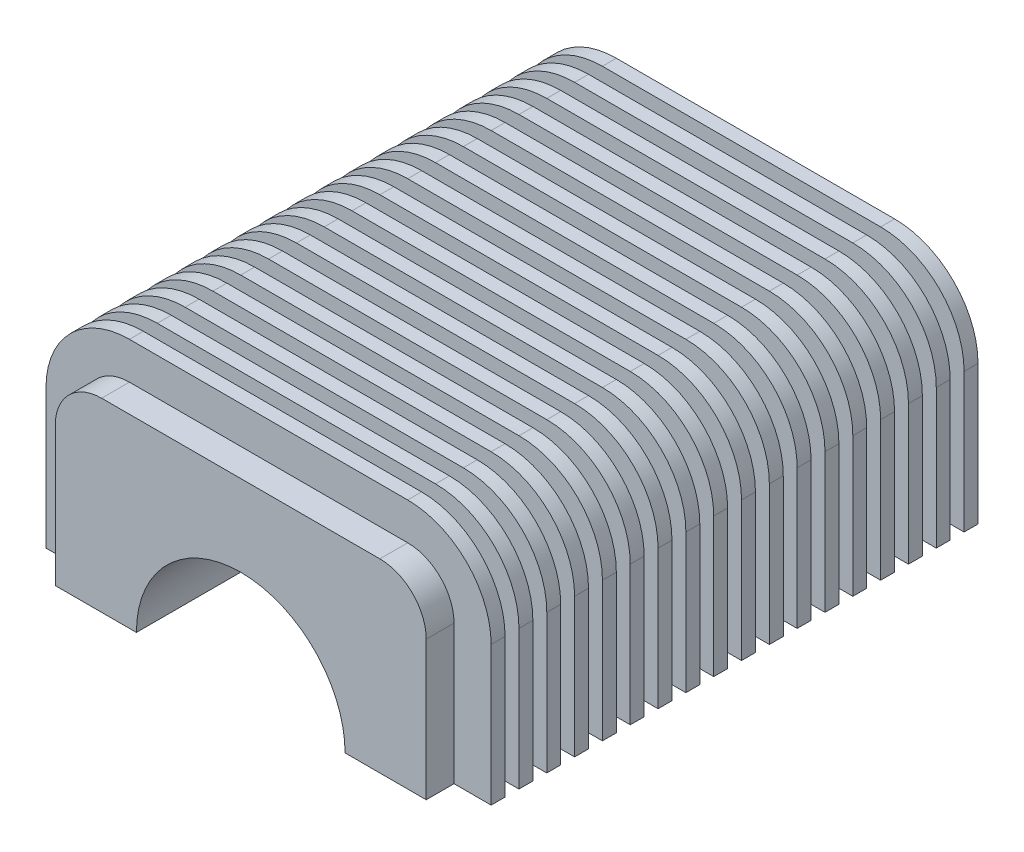
SolidWorks part; units mm, degrees
ref_plane "Płaszczyzna przednia" through (0, 0, 0) normal (0, 0, 1) x (1, 0, 0)
ref_plane "Płaszczyzna górna" through (0, 0, 0) normal (0, 1, 0) x (1, 0, 0)
ref_plane "Płaszczyzna prawa" through (0, 0, 0) normal (1, 0, 0) x (0, 0, -1)
sketch "Szkic1" plane through (0, 0, 0) normal (0, 0, 1) x (1, 0, 0)
  line L0 (-22.5, 0) -> (-40, 0)
  line L1 (22.5, 0) -> (40, 0)
  line L2 (-40, 0) -> (-40, 40)
  line L3 (-40, 40) -> (40, 40)
  line L4 (40, 40) -> (40, 0)
  arc A0 (22.5, 0) -> (-22.5, 0) centre (0, 0) ccw
  dimension "D1" = 45
  dimension "D2" = 17.5
  dimension "D3" = 17.5
  dimension "D4" = 40
extrude "Dodanie-wyciągnięcie1" add sketch "Szkic1" along normal blind 108
fillet "Zaokrąglenie1" radius 10 2 edges at (-40, 40, 54) (40, 40, 54)
sketch "Szkic3" plane through (0, 0, 0) normal (0, 0, -1) x (-1, 0, 0)
  line L0 (48, 0) -> (48, 30)
  line L1 (30, 48) -> (-30, 48)
  line L2 (-48, 30) -> (-48, 0)
  line L3 (-48, 0) -> (-40, 0)
  line L4 (40, 0) -> (48, 0)
  line L5 (40, 0) -> (40, 30)
  line L6 (30, 40) -> (-30, 40)
  line L7 (-40, 30) -> (-40, 0)
  line L8 (-40, 0) -> (-22.5, 0)
  line L9 (22.5, 0) -> (40, 0)
  line L10 (40, 0) -> (40, 30)
  line L11 (30, 40) -> (-30, 40)
  line L12 (-40, 30) -> (-40, 0)
  arc A0 (48, 30) -> (30, 48) centre (30, 30) ccw
  arc A1 (-30, 48) -> (-48, 30) centre (-30, 30) ccw
  arc A3 (40, 30) -> (30, 40) centre (30, 30) ccw
  arc A4 (-30, 40) -> (-40, 30) centre (-30, 30) ccw
  arc A5 (22.5, 0) -> (-22.5, 0) centre (0, 0) ccw
  arc A6 (40, 30) -> (30, 40) centre (30, 30) ccw
  arc A7 (-30, 40) -> (-40, 30) centre (-30, 30) ccw
  dimension "D1" = 0
  dimension "D2" = 8
extrude "Dodanie-wyciągnięcie2" add sketch "Szkic3" along normal blind 3 separate body
pattern_linear "Szyk liniowy1" count 18 spacing 6 along (0, 0, 1) of "Dodanie-wyciągnięcie2"
